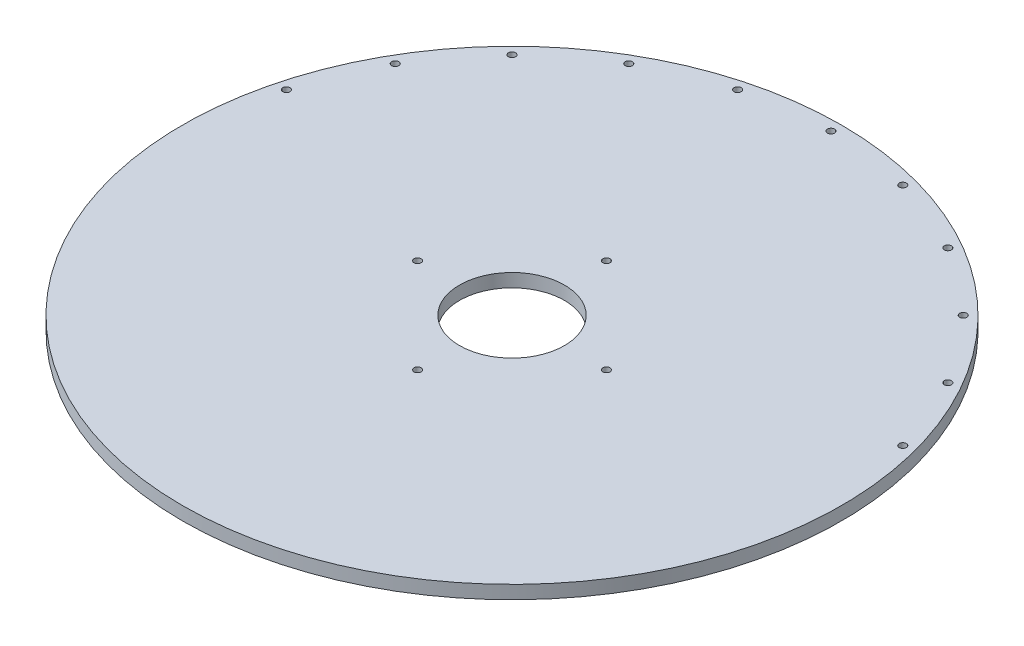
SolidWorks part; units mm, degrees
ref_plane "Front Plane" through (0, 0, 0) normal (0, 0, 1) x (1, 0, 0)
ref_plane "Top Plane" through (0, 0, 0) normal (0, 1, 0) x (1, 0, 0)
ref_plane "Right Plane" through (0, 0, 0) normal (1, 0, 0) x (0, 0, -1)
sketch "Sketch2" plane through (0, 0, 0) normal (0, 1, 0) x (1, 0, 0)
  circle A0 centre (0, 0) radius 65
  circle A1 centre (0, 0) radius 147
  circle A2 centre (0, 0) radius 157
  dimension "D1" = 82
  dimension "D2" = 130
  dimension "D3" = 10
extrude "Boss-Extrude1" add sketch "Sketch2" against normal blind 6.35 contours A2
sketch "Sketch3" plane through (0, 0, 0) normal (0, 1, 0) x (1, 0, 0)
  line L0 (-157, 0) -> (0, 0)
  line L1 (0, 0) -> (157, 0)
  circle A0 centre (0, 0) radius 147 construction
  circle A1 centre (0, 0) radius 157 construction
  circle A2 centre (0, 0) radius 147
  circle A3 centre (0, 0) radius 157
sketch "Sketch4" plane through (0, 0, 0) normal (0, 1, 0) x (1, 0, 0)
  line L0 (0, 0) -> (0, 8) construction
  circle A0 centre (0, 0) radius 25
  dimension "D1" = 8
  dimension "D2" = 50
extrude "Cut-Extrude1" cut sketch "Sketch4" against normal through all
sketch "Sketch5" plane through (0, -6.35, 0) normal (0, -1, 0) x (1, 0, 0)
  line L0 (0, 0) -> (0, 45) construction
  circle A0 centre (0, 45) radius 1.7
  dimension "D1" = 3.4
  dimension "D2" = 45
extrude "Cut-Extrude2" cut sketch "Sketch5" against normal through all
pattern_circular "CirPattern1" count 4 over 360 about axis through (0, 0, 0) along (0, 1, 0) of "Cut-Extrude2"
sketch "Sketch7" plane through (0, 0, 0) normal (0, 1, 0) x (1, 0, 0)
  line L0 (0, 0) -> (-157, 0) construction
  line L1 (-151.6504, 40.6346) -> (-141.9911, 38.0464) construction
  circle A1 centre (0, 0) radius 147 construction
  circle A2 centre (0, 0) radius 147 construction
  circle A3 centre (0, 0) radius 157 construction
  circle A4 centre (-146.8207, 39.3405) radius 1.7
  dimension "D2" = 3.4
  dimension "D1" = 15
extrude "Cut-Extrude4" cut sketch "Sketch7" against normal through all
pattern_circular "CirPattern2" count 11 every 15 about axis through (0, 0, 0) along (0, 1, 0) of "Cut-Extrude4"
